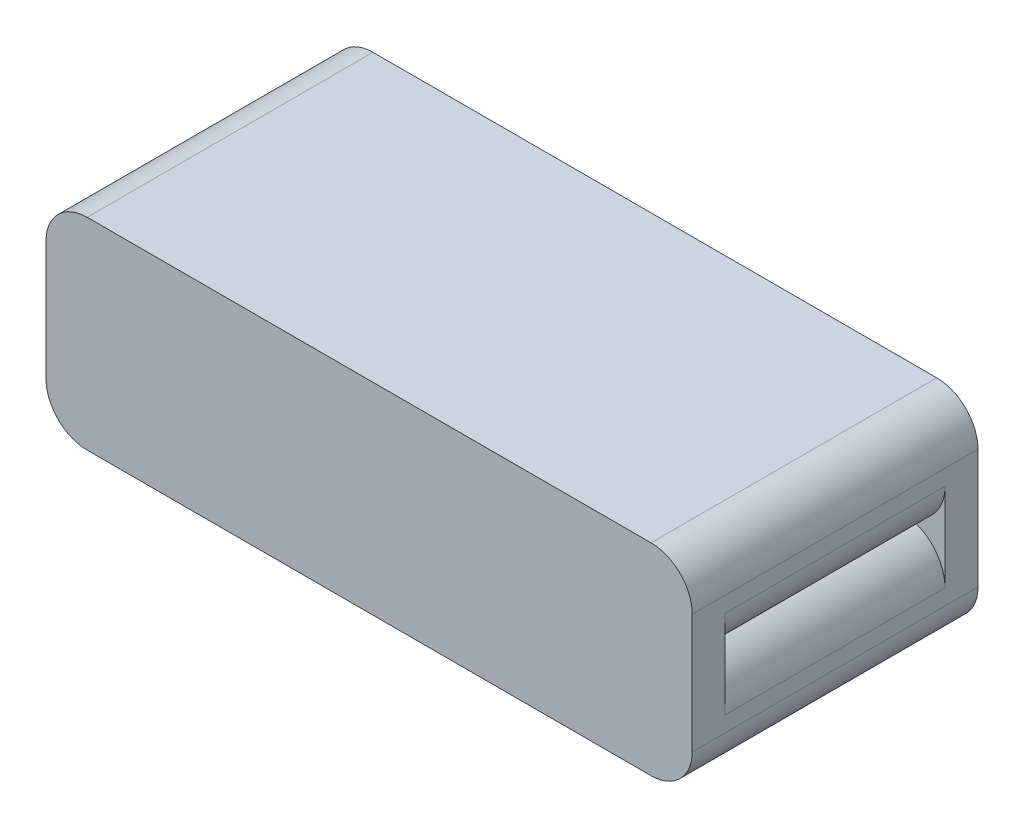
SolidWorks part; units mm, degrees
ref_plane "Front Plane" through (0, 0, 0) normal (0, 0, 1) x (1, 0, 0)
ref_plane "Top Plane" through (0, 0, 0) normal (0, 1, 0) x (1, 0, 0)
ref_plane "Right Plane" through (0, 0, 0) normal (1, 0, 0) x (0, 0, -1)
sketch "Sketch1" plane through (0, 0, 0) normal (0, 1, 0) x (1, 0, 0)
  line L0 (0, -55) -> (0, 55) construction
  line L1 (-74.676, 33.02) -> (74.676, 33.02)
  line L2 (-74.676, 33.02) -> (-74.676, -33.02)
  line L3 (-74.676, -33.02) -> (74.676, -33.02)
  line L4 (74.676, 33.02) -> (74.676, -33.02)
  line L5 (-55, 0) -> (55, 0) construction
  point P4 (0, 33.02)
  point P7 (-74.676, 0)
  dimension "D1" = 149.352
  dimension "D2" = 66.04
extrude "Boss-Extrude1" add sketch "Sketch1" along normal mid plane 46.609
fillet "Fillet1" radius 9.525 4 edges at (-74.676, -23.3045, 0) (-74.676, 23.3045, 0) (74.676, 23.3045, 0) (74.676, -23.3045, 0)
sketch "Sketch2" plane through (0, 0, 0) normal (0, 0, 1) x (1, 0, 0)
  line L0 (-74.676, 13.7795) -> (-74.676, -13.7795) construction
  line L1 (-74.676, 10.16) -> (-74.676, -10.16)
  line L2 (36.322, 0) -> (-36.322, 0) construction
  arc A2 (-74.676, 10.16) -> (-64.516, 0) centre (-64.516, 10.16) ccw
  arc A3 (-64.516, 0) -> (-74.676, -10.16) centre (-64.516, -10.16) ccw
  point P6 (-64.516, 0)
  point P7 (-64.516, 0)
  dimension "D1" = 20.32
extrude "Cut-Extrude1" cut sketch "Sketch2" against normal mid plane 50.8
mirror "Mirror1" about plane through (0, 0, 0) normal (1, 0, 0) of "Cut-Extrude1"
